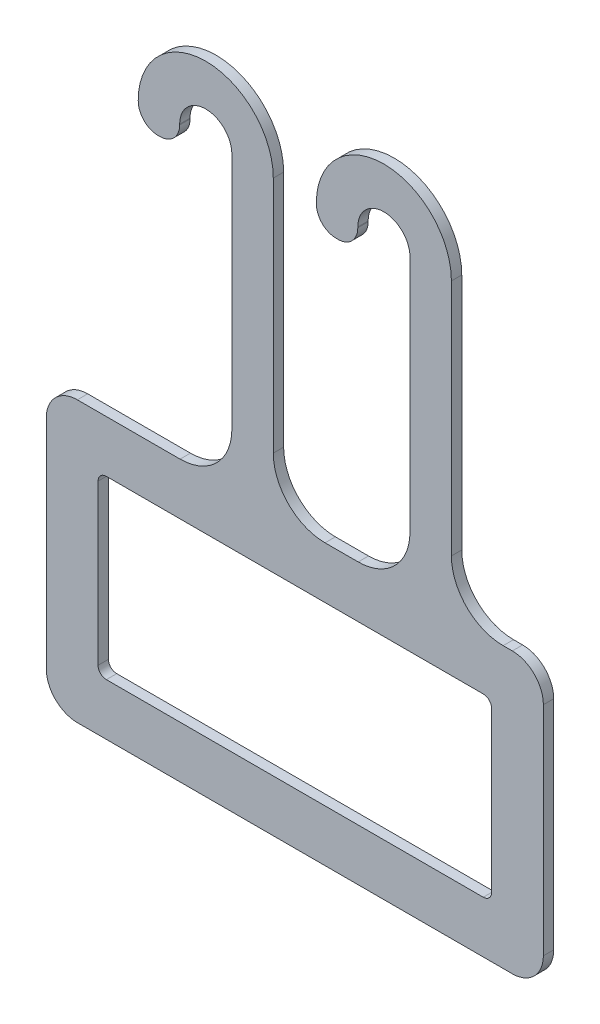
SolidWorks part; units mm, degrees
material "Acrylic (Medium-high impact)"
ref_plane "Front" through (0, 0, 0) normal (0, 0, 1) x (1, 0, 0)
ref_plane "Top" through (0, 0, 0) normal (0, 1, 0) x (1, 0, 0)
ref_plane "Right" through (0, 0, 0) normal (1, 0, 0) x (0, 0, -1)
sketch "Sketch1" plane through (0, 0, 0) normal (0, 0, 1) x (1, 0, 0)
  line L0 (0, 0) -> (0, -42.8625) construction
  line L1 (-57.785, 26.9875) -> (57.785, 26.9875)
  line L2 (-60.325, 24.4475) -> (-60.325, -24.4475)
  line L3 (-57.785, -26.9875) -> (57.785, -26.9875)
  line L4 (60.325, 24.4475) -> (60.325, -24.4475)
  line L5 (-60.325, 26.9875) -> (60.325, -26.9875) construction
  line L6 (-60.325, -26.9875) -> (60.325, 26.9875) construction
  line L7 (-66.675, 42.8625) -> (-35.179, 42.8625)
  line L8 (-76.2, 33.3375) -> (-76.2, -33.3375)
  line L9 (-66.675, -42.8625) -> (66.675, -42.8625)
  line L10 (76.2, 33.3375) -> (76.2, -33.3375)
  line L11 (-76.2, 42.8625) -> (76.2, -42.8625) construction
  line L12 (-76.2, -42.8625) -> (76.2, 42.8625) construction
  line L13 (-12.954, 42.8625) -> (-12.954, 131.7625) construction
  line L14 (41.656, 42.8625) -> (41.656, 131.7625) construction
  line L15 (-12.954, 131.7625) -> (41.656, 131.7625) construction
  line L16 (-27.305, 131.7625) -> (27.305, 131.7625) construction
  line L17 (-6.604, 58.7375) -> (-6.604, 131.7625)
  line L18 (48.006, 58.7375) -> (48.006, 131.7625)
  line L19 (-19.304, 58.7375) -> (-19.304, 131.7625)
  line L20 (35.306, 58.7375) -> (35.306, 131.7625)
  line L21 (9.271, 42.8625) -> (19.431, 42.8625)
  line L22 (63.881, 42.8625) -> (66.675, 42.8625)
  line L23 (48.006, 42.8625) -> (48.006, 131.7625) construction
  line L24 (35.306, 42.8625) -> (35.306, 131.7625) construction
  line L25 (-6.604, 42.8625) -> (-6.604, 131.7625) construction
  line L26 (-19.304, 42.8625) -> (-19.304, 131.7625) construction
  line L27 (19.304, 131.7625) -> (6.604, 131.7625) construction
  line L28 (-35.306, 131.7625) -> (-48.006, 131.7625) construction
  line L29 (-35.306, 131.7625) -> (-35.306, 122.0326) construction
  line L30 (-27.305, 131.7625) -> (-27.305, -42.8625) construction
  line L31 (-27.305, 131.7625) -> (-27.305, 152.4635) construction
  line L32 (-27.305, 152.4635) -> (27.305, 152.4635) construction
  line L33 (27.305, 152.4635) -> (27.305, 131.7625) construction
  line L34 (0, 152.4635) -> (0, 0) construction
  line L35 (-48.006, 131.7625) -> (-48.006, 125.4125)
  line L36 (-48.006, 125.4125) -> (-35.306, 125.4125)
  line L37 (-35.306, 125.4125) -> (-35.306, 131.7625)
  line L38 (6.604, 131.7625) -> (6.604, 125.4125)
  line L39 (6.604, 125.4125) -> (19.304, 125.4125)
  line L40 (19.304, 125.4125) -> (19.304, 131.7625)
  arc A0 (60.325, 24.4475) -> (57.785, 26.9875) centre (57.785, 24.4475) ccw
  arc A1 (60.325, -24.4475) -> (57.785, -26.9875) centre (57.785, -24.4475) cw
  arc A2 (-57.785, -26.9875) -> (-60.325, -24.4475) centre (-57.785, -24.4475) cw
  arc A3 (-57.785, 26.9875) -> (-60.325, 24.4475) centre (-57.785, 24.4475) ccw
  arc A4 (63.881, 42.8625) -> (48.006, 58.7375) centre (63.881, 58.7375) cw
  arc A5 (35.306, 58.7375) -> (19.431, 42.8625) centre (19.431, 58.7375) cw
  arc A6 (9.271, 42.8625) -> (-6.604, 58.7375) centre (9.271, 58.7375) cw
  arc A7 (-19.304, 58.7375) -> (-35.179, 42.8625) centre (-35.179, 58.7375) cw
  arc A8 (76.2, 33.3375) -> (66.675, 42.8625) centre (66.675, 33.3375) ccw
  arc A9 (76.2, -33.3375) -> (66.675, -42.8625) centre (66.675, -33.3375) cw
  arc A10 (-66.675, -42.8625) -> (-76.2, -33.3375) centre (-66.675, -33.3375) cw
  arc A11 (-66.675, 42.8625) -> (-76.2, 33.3375) centre (-66.675, 33.3375) ccw
  arc A12 (-19.304, 131.7625) -> (-35.306, 131.7625) centre (-27.305, 131.7625) ccw
  arc A13 (-6.604, 131.7625) -> (-48.006, 131.7625) centre (-27.305, 131.7625) ccw
  arc A14 (35.306, 131.7625) -> (19.304, 131.7625) centre (27.305, 131.7625) ccw
  arc A15 (48.006, 131.7625) -> (6.604, 131.7625) centre (27.305, 131.7625) ccw
  point P0 (0, 0)
  point P18 (0, 0)
  dimension "D3" = 2.54
  dimension "D10" = 15.875
  dimension "D11" = 9.525
  dimension "D1" = 120.65
  dimension "D2" = 53.975
  dimension "D4" = 15.875
  dimension "D5" = 15.875
  dimension "D6" = 54.61
  dimension "D7" = 88.9
  dimension "D12" = 6.35
  dimension "D13" = 41.402
  dimension "D8" = 6.35
  dimension "D9" = 6.35
extrude "Boss-Extrude1" add sketch "Sketch1" along normal blind 3.175
fillet "Fillet1" radius 6.096 4 edges at (19.304, 125.4125, 1.5875) (6.604, 125.4125, 1.5875) (-35.306, 125.4125, 1.5875) (-48.006, 125.4125, 1.5875)
ref_plane "Plane1" through (0, 0, 0) normal (0, -1, 0) x (-1, 0, 0)
